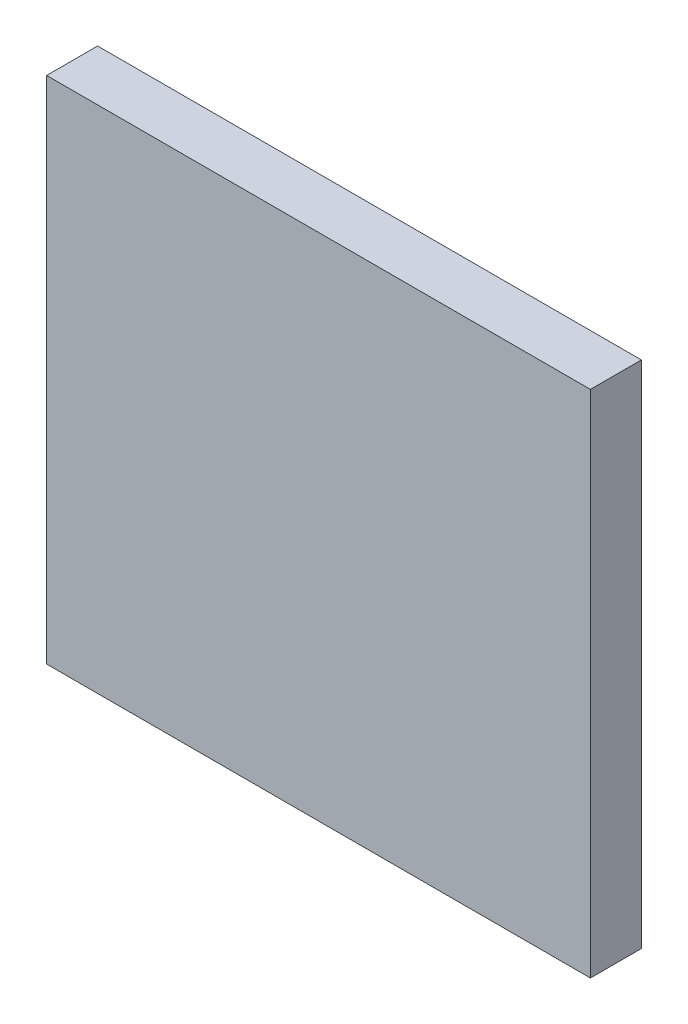
SolidWorks part; units mm, degrees
ref_plane "Płaszczyzna przednia" through (0, 0, 0) normal (0, 0, 1) x (1, 0, 0)
ref_plane "Płaszczyzna górna" through (0, 0, 0) normal (0, 1, 0) x (1, 0, 0)
ref_plane "Płaszczyzna prawa" through (0, 0, 0) normal (1, 0, 0) x (0, 0, -1)
sketch "Szkic1" plane through (0, 0, 0) normal (0, 0, 1) x (1, 0, 0)
  line L1 (-310, 1510) -> (10, 1510)
  line L2 (-310, 1510) -> (-310, 1810)
  line L3 (-310, 1810) -> (10, 1810)
  line L4 (10, 1510) -> (10, 1810)
extrude "Dodanie-wyciągnięcie1" add sketch "Szkic1" along normal blind 30
